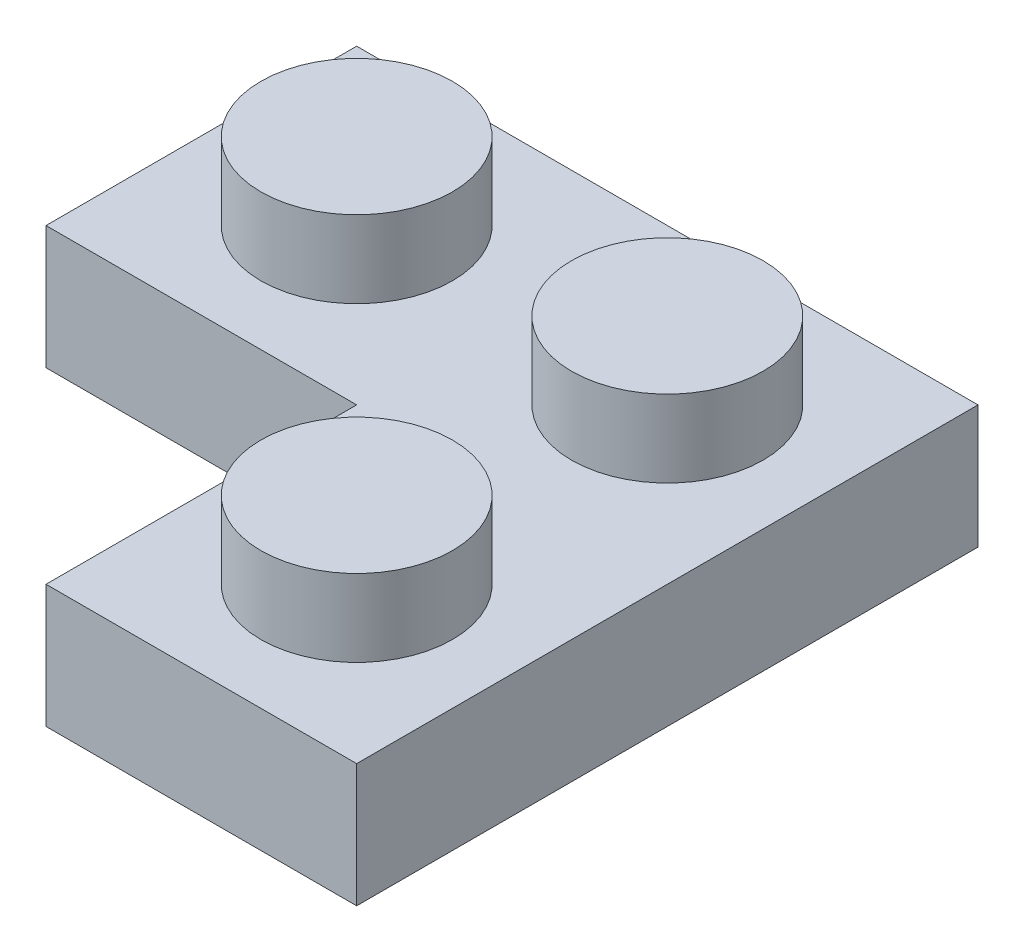
SolidWorks part; units mm, degrees
ref_plane "Front Plane" through (0, 0, 0) normal (0, 0, 1) x (1, 0, 0)
ref_plane "Top Plane" through (0, 0, 0) normal (0, 1, 0) x (1, 0, 0)
ref_plane "Right Plane" through (0, 0, 0) normal (1, 0, 0) x (0, 0, -1)
sketch "Sketch1" plane through (0, 0, 0) normal (0, 1, 0) x (1, 0, 0)
  line L0 (0, 0) -> (0, -7.945)
  line L1 (0, -7.945) -> (7.945, -7.945)
  line L2 (7.945, -7.945) -> (7.945, 7.945)
  line L3 (7.945, 7.945) -> (-7.945, 7.945)
  line L4 (-7.945, 7.945) -> (-7.945, 0)
  line L5 (-7.945, 0) -> (0, 0)
  point P8 (7.945, 0)
  point P10 (0, 7.945)
  dimension "D1" = 15.89
  dimension "D2" = 15.89
extrude "Boss-Extrude1" add sketch "Sketch1" against normal blind 3.15
sketch "Sketch2" plane through (0, 0, 0) normal (0, 1, 0) x (1, 0, 0)
  line L1 (7.945, -7.945) -> (7.945, 7.945) construction
  line L2 (7.945, 7.945) -> (-7.945, 7.945) construction
  line L3 (0, -7.945) -> (7.945, -7.945) construction
  line L4 (-7.945, 7.945) -> (-7.945, 0) construction
  circle A0 centre (3.9725, 3.9725) radius 2.45
  circle A1 centre (3.9725, -3.9725) radius 2.45
  circle A2 centre (-3.9725, 3.9725) radius 2.45
  dimension "D1" = 3.9725
  dimension "D3" = 4.9
  dimension "D4" = 3.9725
  dimension "D6" = 4.9
  dimension "D9" = 4.9
  dimension "D2" = 3.9725
  dimension "D5" = 3.9725
  dimension "D7" = 3.9725
  dimension "D8" = 3.9725
extrude "Boss-Extrude2" add sketch "Sketch2" along normal blind 1.97
shell "Shell1" thickness 1.55
sketch "Sketch3" plane through (0, -1.55, 0) normal (0, -1, 0) x (1, 0, 0)
  line L1 (-7.945, 0) -> (0, 0) construction
  line L2 (7.945, 7.945) -> (7.945, -7.945) construction
  circle A0 centre (0, -3.975) radius 1.48
  circle A1 centre (0, -3.975) radius 0.54
  circle A2 centre (3.97, 0) radius 1.48
  circle A3 centre (3.97, 0) radius 0.54
  dimension "D2" = 3.975
  dimension "D3" = 2.96
  dimension "D4" = 2.96
  dimension "D5" = 1.08
  dimension "D6" = 1.08
  dimension "D1" = 3.975
extrude "Boss-Extrude3" add sketch "Sketch3" along normal offset from surface (1.4 mm away) 0.2 up to face at (0, -3.15, 0)
